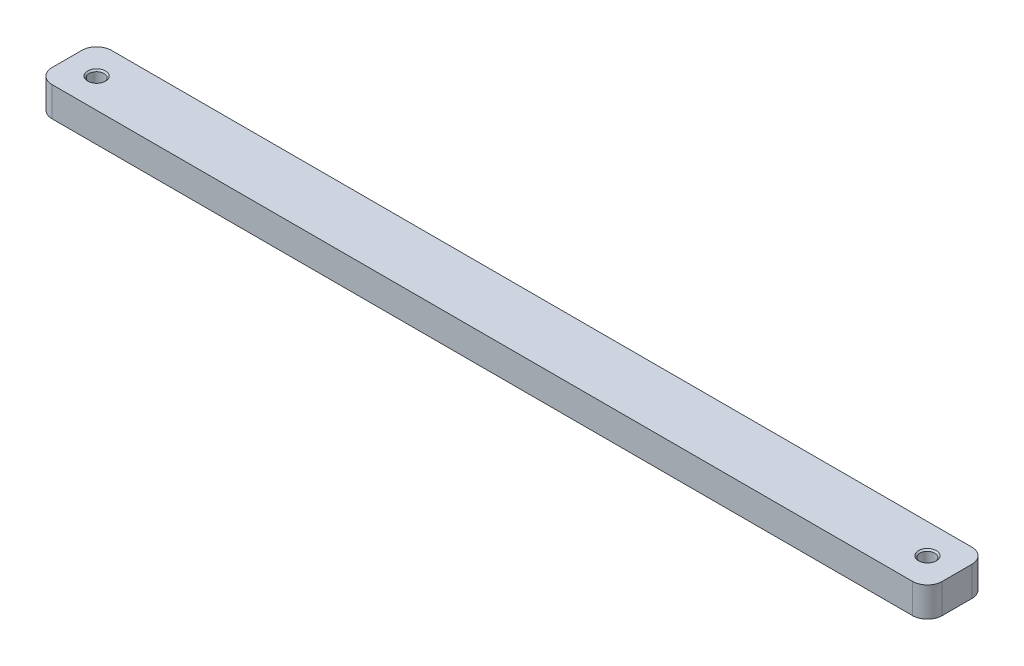
SolidWorks part; units mm, degrees
ref_plane "Piano frontale" through (0, 0, 0) normal (0, 0, 1) x (1, 0, 0)
ref_plane "Piano superiore" through (0, 0, 0) normal (0, 1, 0) x (1, 0, 0)
ref_plane "Piano destro" through (0, 0, 0) normal (1, 0, 0) x (0, 0, -1)
sketch "Schizzo1" plane through (0, 0, 0) normal (0, 1, 0) x (1, 0, 0)
  line L1 (-150, 10) -> (150, 10)
  line L2 (-150, 10) -> (-150, -10)
  line L3 (-150, -10) -> (150, -10)
  line L4 (150, 10) -> (150, -10)
  line L5 (-150, 10) -> (150, -10) construction
  line L6 (-150, -10) -> (150, 10) construction
  point P0 (0, 0)
  dimension "D1" = 300
  dimension "D2" = 20
extrude "Estrusione-Estrusione1" add sketch "Schizzo1" along normal blind 10
hole_wizard "Foro filettato M6-5" positions "Schizzo14" profile "Schizzo13" tap size "M6" standard "ISO" end condition through all
sketch "Schizzo14" plane through (0, 10, 0) normal (0, 1, 0) x (1, 0, 0)
  line L0 (150, 10) -> (-150, 10) construction
  line L1 (150, -10) -> (150, 10) construction
  line L2 (-150, 10) -> (-150, -10) construction
  point P0 (-140, 0)
  point P2 (140, 0)
  point P12 (150, -2.4395)
  dimension "D1" = 10
  dimension "D2" = 10
  dimension "D3" = 10
  dimension "D4" = 10
sketch "Schizzo13" plane through (-140, 10, 0) normal (1, 0, 0) x (0, 0, 1)
  line L0 (0, 0) -> (0, 10)
  line L1 (0, 10) -> (2.5, 10)
  line L2 (2.5, 10) -> (2.5, 0.5)
  line L3 (2.5, 0.5) -> (3, 0)
  line L5 (3, 0) -> (0, 0)
  line L6 (-2.5, 0.5) -> (-3, 0) construction
  line L11 (0, -6.35) -> (0, 107.95) construction
  dimension "Thru Tap Drill Dia." = 5
  dimension "Thru Tap Drill Depth" = 10
  dimension "Near C'Sink Dia." = 6
  dimension "Near C'Sink Angle" = 90
cosmetic thread "Filettatura del foro6" parameters "D2"=6
cosmetic thread "Filettatura del foro7" parameters "D2"=6
fillet "Raccordo1" radius 5 4 edges at (150, 5, 10) (150, 5, -10) (-150, 5, -10) (-150, 5, 10)
